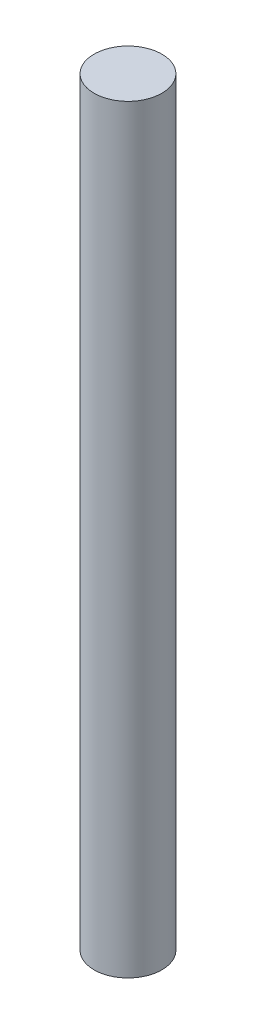
SolidWorks part; units mm, degrees
material "Alloy Steel"
ref_plane "Front Plane" through (0, 0, 0) normal (0, 0, 1) x (1, 0, 0)
ref_plane "Top Plane" through (0, 0, 0) normal (0, 1, 0) x (1, 0, 0)
ref_plane "Right Plane" through (0, 0, 0) normal (1, 0, 0) x (0, 0, -1)
sketch "Sketch2" plane through (0, 0, 0) normal (0, 1, 0) x (1, 0, 0)
  circle A0 centre (0, 0) radius 2.5
  dimension "D1" = 5
extrude "Boss-Extrude1" add sketch "Sketch2" along normal mid plane 56
